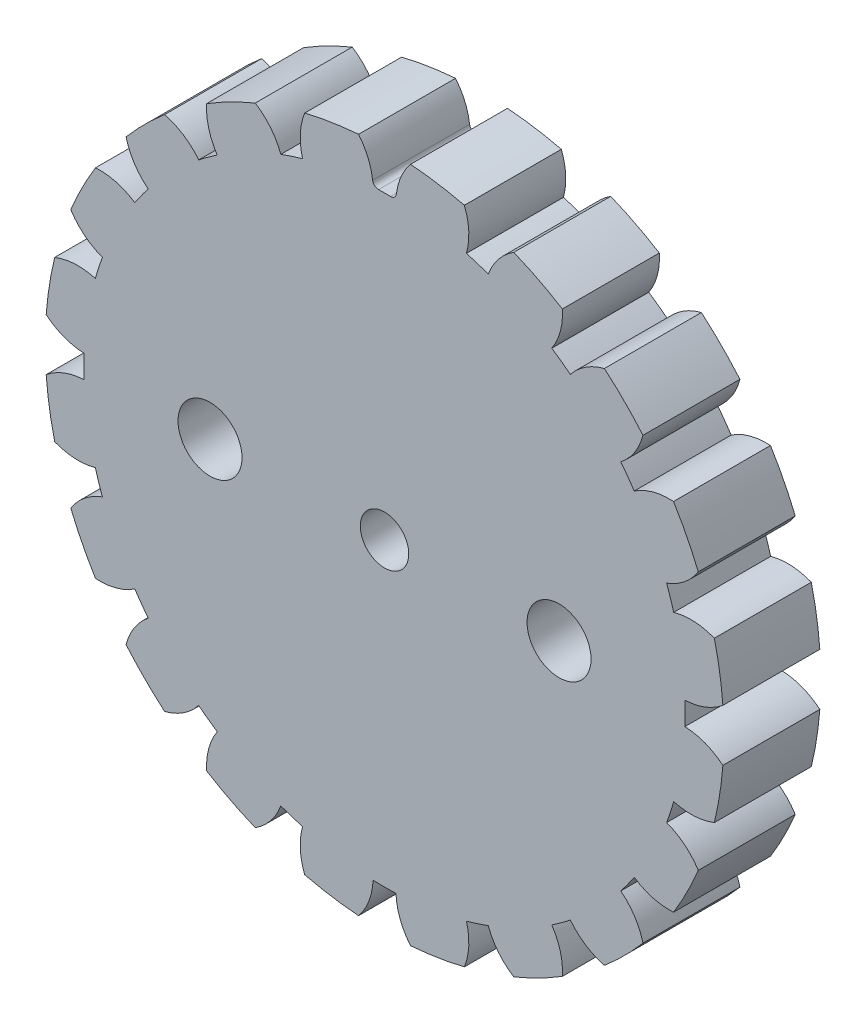
SolidWorks part; units mm, degrees
ref_plane "Front" through (0, 0, 0) normal (0, 0, 1) x (1, 0, 0)
ref_plane "Top" through (0, 0, 0) normal (0, 1, 0) x (1, 0, 0)
ref_plane "Right" through (0, 0, 0) normal (1, 0, 0) x (0, 0, -1)
sketch "Sketch1" plane through (0, 0, 0) normal (0, 0, 1) x (1, 0, 0)
  circle A0 centre (0, 0) radius 15.5
  circle A1 centre (0, 0) radius 17.5
  circle A2 centre (0, 0) radius 16.5
  dimension "D1" = 35
  dimension "D2" = 31
  dimension "D3" = 33
extrude "Boss-Extrude1" add sketch "Sketch1" along normal mid plane 5 contours A1
sketch "Sketch3" plane through (0, 0, 0) normal (0, 0, 1) x (1, 0, 0)
  line L0 (0, 0) -> (0, 17.5) construction
  line L1 (-0.7851, 16.4813) -> (0.7851, 16.4813) construction
  line L2 (-1.4977, 18.4393) -> (0, 14.3243) construction
  line L3 (0, 0) -> (1.6635, 17.4208) construction
  line L4 (0.7851, 16.4813) -> (2.3482, 16.3321) construction
  line L5 (0, 0) -> (-0.5905, 15.4887) construction
  circle A0 centre (0, 0) radius 17.5 construction
  arc A1 (-2.4899, 18.3317) -> (-0.5905, 15.4887) centre (-3.854, 15.3643) cw
  arc A2 (2.4899, 18.3317) -> (0.5905, 15.4887) centre (3.854, 15.3643) ccw
  arc A3 (0.5905, 15.4887) -> (-0.5905, 15.4887) centre (0, 0) ccw
  circle A4 centre (0, 0) radius 15.5 construction
  circle A6 centre (0, 0) radius 16.5 construction
  circle A7 centre (0, 0) radius 18.5
  arc A8 (2.4899, 18.3317) -> (-2.4899, 18.3317) centre (0, 0) ccw
  circle A9 centre (0, 0) radius 17.5 construction
  dimension "D3" = 5.455
  dimension "D2" = 20
  dimension "D1" = 1
extrude "Cut-Extrude1" cut sketch "Sketch3" against normal through all both and the other way through all
fillet "Fillet2" radius 0.3 2 edges at (0.5905, 15.4887, 0) (-0.5905, 15.4887, 0)
pattern_circular "CirPattern1" count 20 over 360 about axis through (0, 0, 0) along (0, 0, 1) of "Cut-Extrude1"
sketch "Sketch4" plane through (0, 0, 0) normal (0, 0, 1) x (1, 0, 0)
  circle A0 centre (0, 0) radius 1.25
  dimension "D1" = 2.5
extrude "Through_Center_Hole" cut sketch "Sketch4" against normal through all both and the other way through all
sketch "Sketch5" plane through (0, 0, 0) normal (0, 0, 1) x (1, 0, 0)
  line L0 (-9, 0) -> (9, 0) construction
  circle A0 centre (9, 0) radius 1.65
  circle A1 centre (-9, 0) radius 1.65
  dimension "D2" = 3.3
  dimension "D1" = 18
extrude "To_Knuckle_Mount" cut sketch "Sketch5" against normal through all both and the other way through all
equation "\"od\"= 35'outside diameter"
equation "\"n\"= 33'number of teeth"
equation "\"m\"= \"od\" / ( \"n\" + 2 )'module"
equation "\"p\"= \"m\" * pi'pitch"
equation "\"d\"= \"m\" * \"n\"'primitive diameter"
equation "\"da\"= \"d\" + 2 * \"m\"'head diamater"
equation "\"df\"= \"d\" - 2 * \"m\"'foot diameter"
equation "\"D1@Sketch1\"=\"od\""
equation "\"D2@Sketch1\"=\"df\""
equation "\"D3@Sketch1\"=\"d\""
equation "\"D3@Sketch3\"=180/\"n\""
equation "\"D1@Fillet2\"=.3*\"m\""
